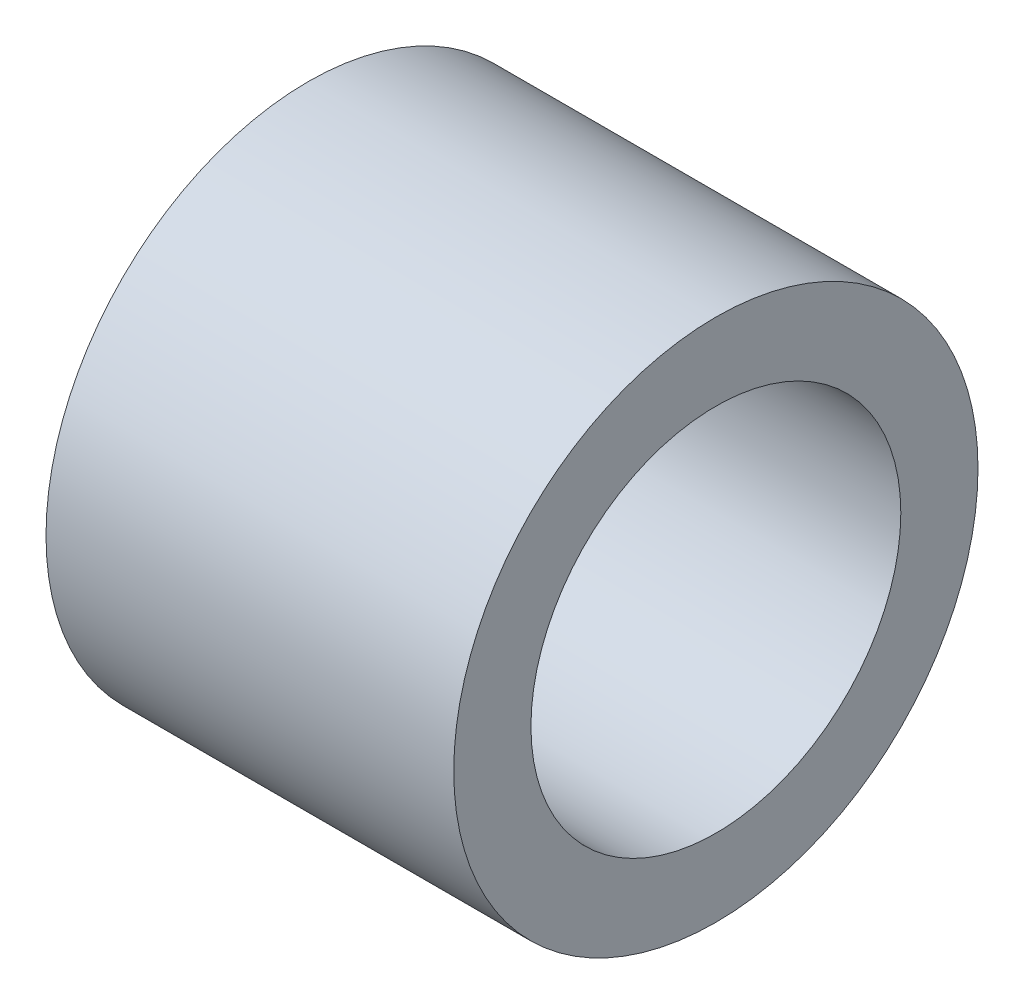
SolidWorks part; units mm, degrees
material "Copper"
ref_plane "Front Plane" through (0, 0, 0) normal (0, 0, 1) x (1, 0, 0)
ref_plane "Top Plane" through (0, 0, 0) normal (0, 1, 0) x (1, 0, 0)
ref_plane "Right Plane" through (0, 0, 0) normal (1, 0, 0) x (0, 0, -1)
sketch "Axial profile (mm)" plane through (0, 0, 0) normal (0, 0, 1) x (1, 0, 0)
  line L0 (-110, 0) -> (75, 0) construction
  line L1 (97, 2.4) -> (99, 2.4)
  line L2 (99, 2.4) -> (99, 3.175)
  line L3 (99, 3.175) -> (104, 3.175)
  line L4 (104, 3.175) -> (104, 4.5)
  line L5 (104, 4.5) -> (97, 4.5)
  line L6 (97, 4.5) -> (97, 2.4)
revolve "Full revolution" add sketch "Axial profile (mm)" angle 360 about L0
